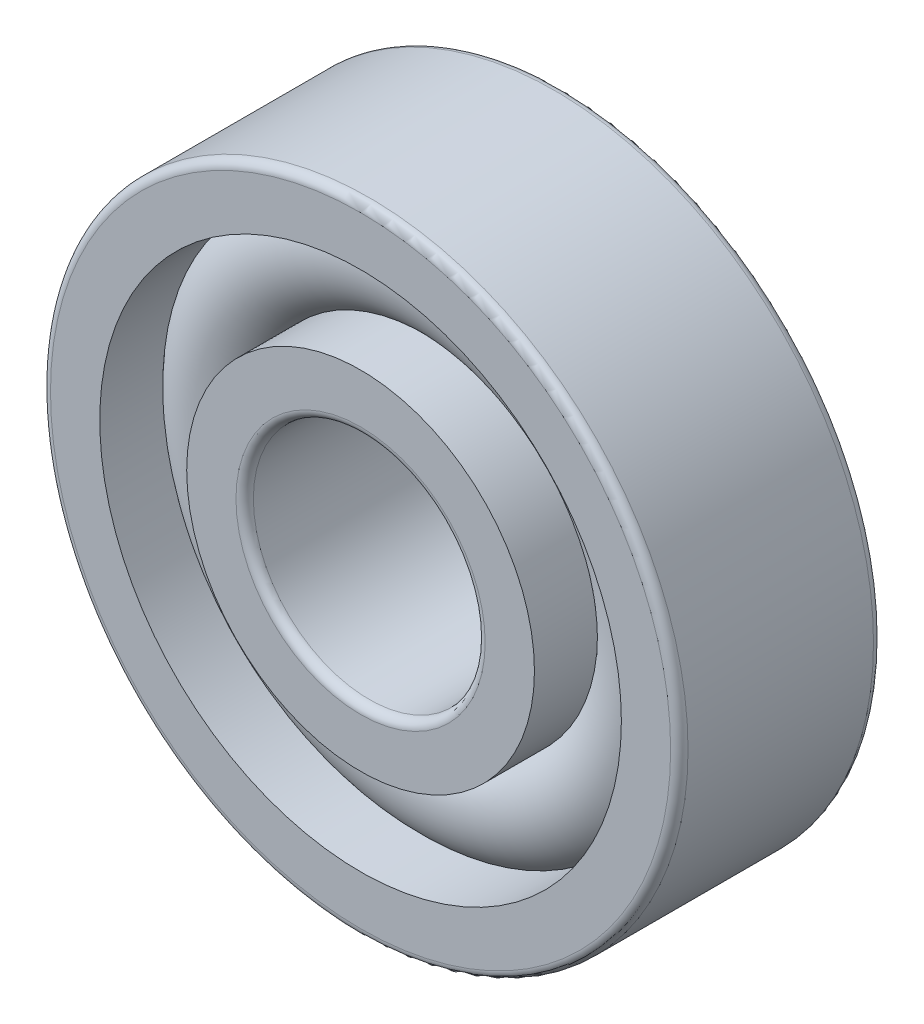
SolidWorks part; units mm, degrees
material "AISI 1010 Steel, hot rolled bar"
ref_plane "Front" through (0, 0, 0) normal (0, 0, 1) x (1, 0, 0)
ref_plane "Top" through (0, 0, 0) normal (0, 1, 0) x (1, 0, 0)
ref_plane "Right" through (0, 0, 0) normal (1, 0, 0) x (0, 0, -1)
sketch "Sketch1" plane through (0, 0, 0) normal (1, 0, 0) x (0, 0, -1)
  line L0 (0, 13.3543) -> (0, 0) construction
  line L1 (0, 0) -> (18.5098, 0) construction
  line L2 (-3.5, 6) -> (-3.5, 4.3)
  line L3 (-3.2, 4) -> (3.2, 4)
  line L4 (3.5, 4.3) -> (3.5, 6)
  line L5 (3.5, 6) -> (1.3229, 6)
  line L6 (0, 7.5) -> (7.5033, 7.5) construction
  line L7 (-3.5, 6) -> (-1.3229, 6)
  line L8 (-3.5, 9) -> (-1.3229, 9)
  line L9 (-3.5, 9) -> (-3.5, 10.7)
  line L10 (-3.2, 11) -> (3.2, 11)
  line L11 (3.5, 10.7) -> (3.5, 9)
  line L12 (3.5, 9) -> (1.3229, 9)
  arc A0 (-3.5, 4.3) -> (-3.2, 4) centre (-3.2, 4.3) ccw
  arc A1 (3.2, 4) -> (3.5, 4.3) centre (3.2, 4.3) ccw
  arc A2 (1.3229, 6) -> (1.3229, 9) centre (0, 7.5) ccw
  arc A3 (-3.5, 10.7) -> (-3.2, 11) centre (-3.2, 10.7) cw
  arc A4 (3.2, 11) -> (3.5, 10.7) centre (3.2, 10.7) cw
  arc A5 (-1.3229, 9) -> (-1.3229, 6) centre (0, 7.5) ccw
  dimension "D1" = 4
  dimension "D3" = 0.3
  dimension "D2" = 8
  dimension "D4" = 3
  dimension "D5" = 22
  dimension "D6" = 7
revolve "Revolve1" add sketch "Sketch1" angle 360 about L1
